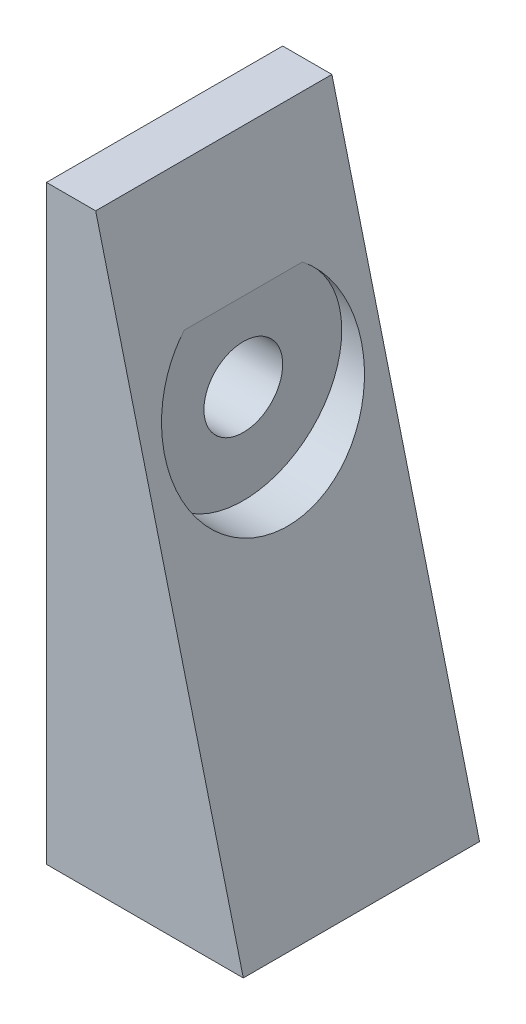
SolidWorks part; units mm, degrees
ref_plane "Alzado" through (0, 0, 0) normal (0, 0, 1) x (1, 0, 0)
ref_plane "Planta" through (0, 0, 0) normal (0, 1, 0) x (1, 0, 0)
ref_plane "Vista lateral" through (0, 0, 0) normal (1, 0, 0) x (0, 0, -1)
sketch "Croquis2" plane through (0, 0, 0) normal (0, 0, 1) x (1, 0, 0)
  line L0 (0, 0) -> (0, 30)
  line L2 (10, 0) -> (0, 0)
  line L3 (0, 30) -> (2.5, 30)
  line L4 (2.5, 30) -> (10, 0)
  dimension "D1" = 10
  dimension "D2" = 30
  dimension "D3" = 2.5
extrude "Saliente-Extruir1" add sketch "Croquis2" along normal mid plane 12
sketch "Croquis3" plane through (0, 0, 0) normal (-1, 0, 0) x (0, 0, 1)
  line L1 (6, 30) -> (-6, 30) construction
  circle A0 centre (0, 20) radius 2
  point P2 (0, 2.0117)
  point P5 (0, 0)
  point P7 (0, 28)
  dimension "D1" = 4
  dimension "D2" = 10
extrude "Cortar-Extruir1" cut sketch "Croquis3" against normal through all
ref_plane "Plano1" through (4, 0, 0) normal (-1, 0, 0) x (0, 0, 1)
sketch "Croquis5" plane through (4, 0, 0) normal (-1, 0, 0) x (0, 0, 1)
  circle A0 centre (0, 20) radius 5
  dimension "D1" = 10
extrude "Cortar-Extruir2" cut sketch "Croquis5" against normal through all
